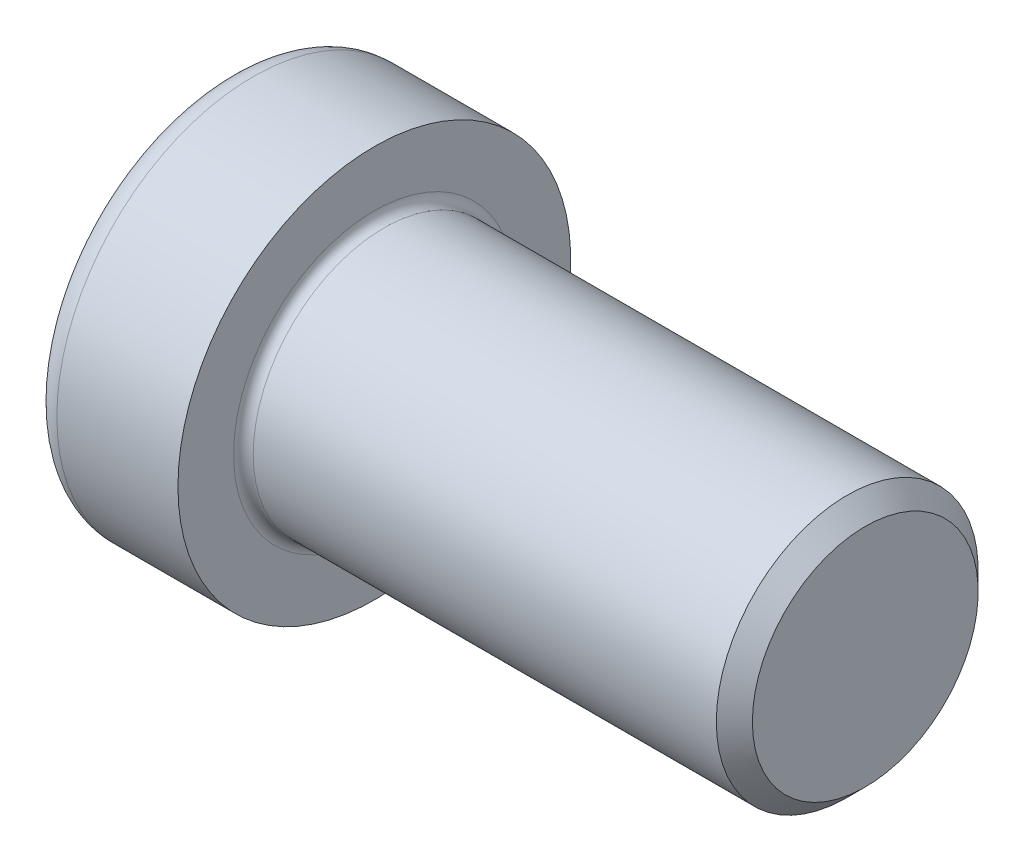
SolidWorks part; units mm, degrees
revolve "Base-Revolve" add sketch "BodySke"
sketch "BodySke" plane through (0, 0, 0) normal (0, 0, 1) x (1, 0, 0)
  line L0 (0, 0) -> (0, 12)
  line L1 (0, 12) -> (9, 12)
  line L2 (9, 12) -> (9, 8)
  line L3 (9, 8) -> (37.8985, 8)
  line L4 (39, 6.8985) -> (39, 0)
  line L5 (39, 0) -> (0, 0)
  line L6 (-31.75, 0) -> (127, 0) construction
  line L8 (39, 6.8985) -> (37.8985, 8)
  line L10 (39, -6.8985) -> (37.8985, -8) construction
  line L11 (11, 4.525) -> (11, -1.825) construction
  line L12 (15, 4.525) -> (15, -1.825) construction
  line L13 (-21, 4.525) -> (-21, -1.825) construction
  dimension "Head_ht" = 9
  dimension "Length" = 30
  dimension "Body_ch_ang" = 45
  dimension "Diameter" = 16
  dimension "Minor_dia" = 13.797
  dimension "Advance" = 2
  dimension "Thread_nom" = 24
  dimension "Thread_length" = 60
  dimension "Head_dia" = 24
cosmetic thread "ThreadCosmetic"
fillet "Fillet1" radius 0.6 1 edges at (9, 0, 8)
fillet "Fillet2" radius 1.6 1 edges at (0, 0, 12)
ref_plane "Plane1" through (0, 0, 0) normal (0, 0, 1) x (1, 0, 0)
ref_plane "Plane2" through (0, 0, 0) normal (0, 1, 0) x (1, 0, 0)
ref_plane "Plane3" through (0, 0, 0) normal (1, 0, 0) x (0, 0, -1)
other "Configuration Table"
sketch "Sketch2" plane through (0, 0, 0) normal (0, 0, 1) x (1, 0, 0)
  line L0 (0, 6) -> (5.5, 6)
  line L1 (5.5, 6) -> (8.9641, 0)
  line L2 (-31.75, 0) -> (127, 0) construction
  line L3 (8.9641, 0) -> (0, 0)
  line L4 (0, 0) -> (0, 6)
  line L6 (0, 0) -> (47.625, 0) construction
  dimension "D1" = 6
  dimension "D2" = 60
  dimension "Depth" = 5.5
revolve "Hex-PreBroach" cut sketch "Sketch2" angle 360 about L6
sketch "Sketch3" plane through (0, 0, 0) normal (-1, 0, 0) x (0, 0.5, 0.866)
  line L0 (3.4641, 6) -> (-3.4641, 6)
  line L1 (-3.4641, 6) -> (-6.9282, 0)
  line L2 (3.4641, 6) -> (6.9282, 0)
  line L3 (3.4641, -6) -> (6.9282, 0)
  line L4 (3.4641, -6) -> (-3.4641, -6)
  line L5 (-3.4641, -6) -> (-6.9282, 0)
  dimension "D1" = 6
  dimension "Hex_size" = 12
extrude "Hex" cut sketch "Sketch3" against normal blind 5.5
sketch "ThdSchSke" plane through (0, 0, 0) normal (0, 0, 1) x (1, 0, 0)
  line L0 (15, -6.8985) -> (14.2287, -8)
  line L1 (15, -6.8985) -> (15.7713, -8)
  line L2 (15.7713, -8) -> (15.7713, -10)
  line L3 (-3.175, 0) -> (5.1513, 0) construction
  line L4 (0, 10.4) -> (0, -10.4) construction
  line L5 (15.7713, -10) -> (14.2287, -10)
  line L6 (14.2287, -10) -> (14.2287, -8)
  dimension "Thread_minor" = 13.797
  dimension "Diameter" = 16
  dimension "Start" = 15
revolve "ThreadSchematic" [suppressed] cut sketch "ThdSchSke" angle 360 about L3
pattern_linear "ThdSchPat" [suppressed]
equation "\"D2@Sketch3\" = \"Hex_size@Sketch3\" / 2"
equation "\"D1@Sketch3\" = \"Hex_size@Sketch3\" / 2"
equation "\"D1@Sketch2\" = \"Hex_size@Sketch3\" / 2"
equation "\"Thread_minor@ThreadCosmetic\"  =  \"Minor_dia@BodySke\""
equation "\"Depth@Sketch2\" =  \"Key_eng@Hex\""
equation "\"Thread_length@ThreadCosmetic\" = ((sgn( (\"Length@BodySke\" - \"Advance@BodySke\" * 3.0) - \"Thread_nom@BodySke\" )-1)*( (\"Length@BodySke\" - \"Advance@BodySke\" * 3.0) - \"Thread_nom@BodySke\" ))/-2+ \"Thread_nom@BodySke\""
equation "\"Thread_minor@ThdSchSke\" = \"Minor_dia@BodySke\""
equation "\"Diameter@ThdSchSke\" = \"Diameter@BodySke\""
equation "\"Overcut@ThdSchSke\" = \"Diameter@BodySke\" * 1.25"
equation "\"Start@ThdSchSke\" = \"Head_ht@BodySke\" + \"Length@BodySke\" - \"Thread_length@ThreadCosmetic\"  '---Non-countersunk---"
equation "\"Num_threads@ThdSchPat\" = int( \"Thread_length@ThreadCosmetic\" / \"Advance@BodySke\" + 0.999 )  + 1"
equation "\"Advance@ThdSchPat\" = \"Thread_length@ThreadCosmetic\" /  (\"Num_threads@ThdSchPat\" - 1) 'relax it"
equation "\"Num_threads@ThdSchPat\" = \"Num_threads@ThdSchPat\" - sgn( \"Num_threads@ThdSchPat\" - 1) '---chamfered tips only---"
